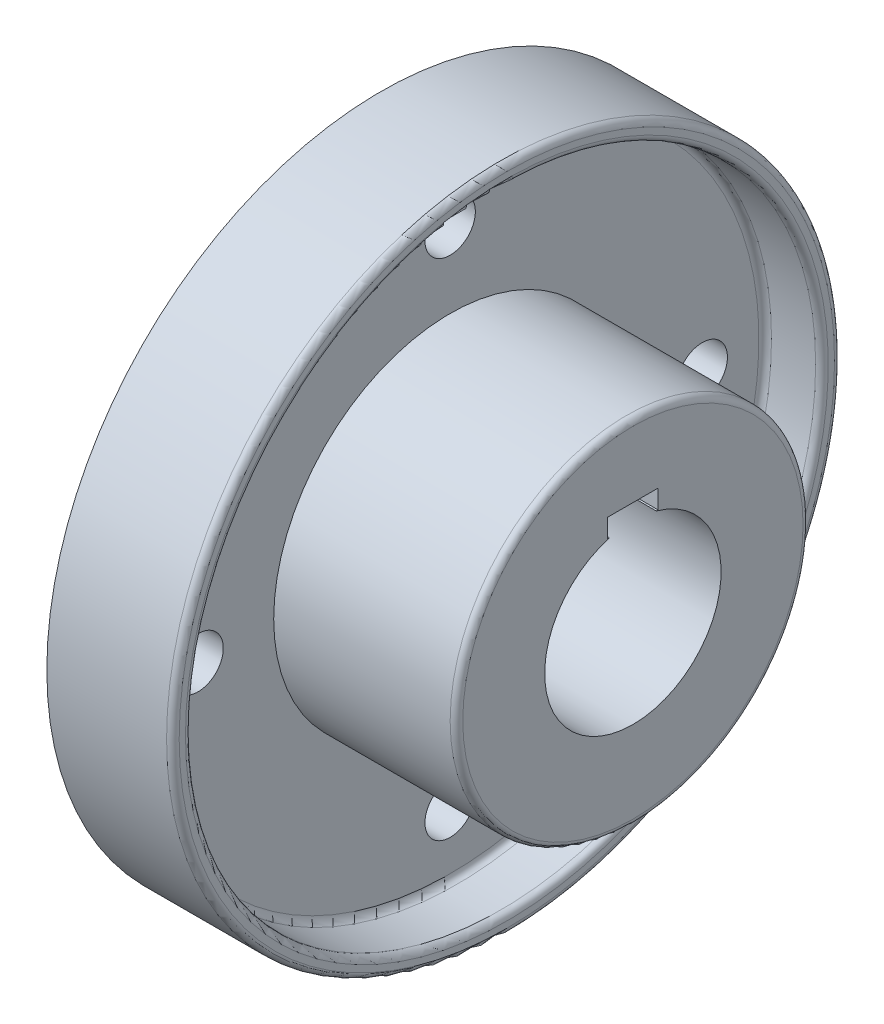
SolidWorks part; units mm, degrees
ref_plane "Front Plane" through (0, 0, 0) normal (0, 0, 1) x (1, 0, 0)
ref_plane "Top Plane" through (0, 0, 0) normal (0, 1, 0) x (1, 0, 0)
ref_plane "Right Plane" through (0, 0, 0) normal (1, 0, 0) x (0, 0, -1)
sketch "Sketch1" plane through (0, 0, 0) normal (0, 0, 1) x (1, 0, 0)
  line L0 (0, 0) -> (80, 0)
  line L1 (80, 0) -> (80, 54)
  line L2 (78, 56) -> (28.2927, 56)
  line L3 (40, 104) -> (40, 102)
  line L4 (38, 106) -> (0, 106)
  line L5 (0, 106) -> (0, 0)
  line L6 (38, 100) -> (24, 100)
  line L7 (22, 98) -> (22, 56)
  line L8 (22, 56) -> (28.2927, 56)
  arc A0 (24, 100) -> (22, 98) centre (24, 98) ccw
  arc A1 (40, 102) -> (38, 100) centre (38, 102) cw
  arc A2 (40, 104) -> (38, 106) centre (38, 104) ccw
  arc A3 (80, 54) -> (78, 56) centre (78, 54) ccw
  point P16 (40, 106)
  point P19 (80, 56)
  dimension "D7" = 2
  dimension "D8" = 2
  dimension "D1" = 80
  dimension "D2" = 56
  dimension "D3" = 106
  dimension "D4" = 22
  dimension "D5" = 40
  dimension "D6" = 6
revolve "Revolve1" add sketch "Sketch1" angle 360 about L0
sketch "Sketch3" plane through (0, 0, 0) normal (-1, 0, 0) x (0, 0, 1)
  circle A0 centre (0, 0) radius 46
  dimension "D1" = 92
extrude "Boss-Extrude1" add sketch "Sketch3" along normal blind 3
sketch "Sketch2" plane through (80, 0, 0) normal (1, 0, 0) x (0, 0, -1)
  circle A0 centre (0, 0) radius 28
  dimension "D1" = 56
extrude "Cut-Extrude1" cut sketch "Sketch2" against normal through all
sketch "Sketch5" plane through (0, 0, 0) normal (-1, 0, 0) x (0, 0, 1)
  line L0 (0, 106) -> (0, -106) construction
  line L1 (106, 0) -> (-106, 0) construction
  circle A0 centre (0, 0) radius 106 construction
  circle A1 centre (0, 80) radius 8
  dimension "D2" = 16
  dimension "D1" = 80
extrude "Cut-Extrude7" cut sketch "Sketch5" against normal through all
pattern_circular "CirPattern2" count 4 over 360 about axis through (0, 0, 0) along (1, 0, 0) of "Cut-Extrude7"
sketch "Sketch7" plane through (-3, 0, 0) normal (-1, 0, 0) x (0, 0, 1)
  line L1 (-8, 27) -> (8, 27)
  line L2 (-8, 27) -> (-8, 33)
  line L3 (-8, 33) -> (8, 33)
  line L4 (8, 27) -> (8, 33)
  line L5 (-8, 27) -> (8, 33) construction
  line L6 (-8, 33) -> (8, 27) construction
  point P0 (0, 30)
  dimension "D1" = 6
  dimension "D2" = 16
  dimension "D3" = 30
extrude "Cut-Extrude8" cut sketch "Sketch7" against normal through all
